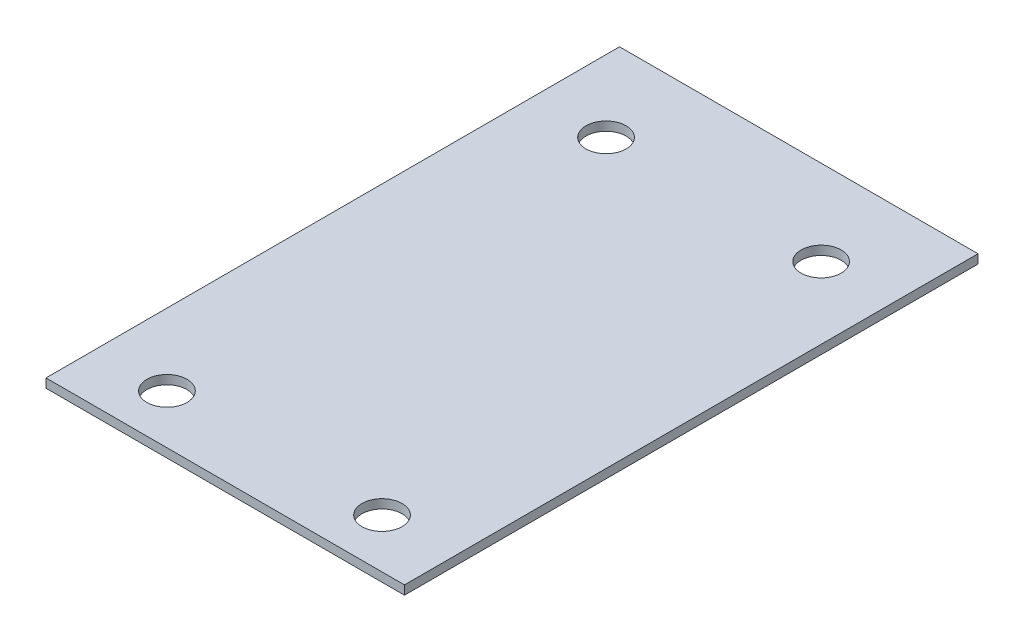
SolidWorks part; units mm, degrees
ref_plane "Front Plane" through (0, 0, 0) normal (0, 0, 1) x (1, 0, 0)
ref_plane "Top Plane" through (0, 0, 0) normal (0, 1, 0) x (1, 0, 0)
ref_plane "Right Plane" through (0, 0, 0) normal (1, 0, 0) x (0, 0, -1)
sketch "Sketch1" plane through (0, 0, 0) normal (0, 1, 0) x (1, 0, 0)
  line L0 (63.5, 203.2) -> (63.5, 0) construction
  line L1 (0, 0) -> (127, 0)
  line L2 (0, 0) -> (0, 203.2)
  line L3 (0, 203.2) -> (127, 203.2)
  line L4 (127, 0) -> (127, 203.2)
  circle A0 centre (25.4, 173.0248) radius 7.112
  circle A1 centre (25.4, 17.4498) radius 7.112
  circle A2 centre (101.6, 17.4498) radius 7.112
  circle A3 centre (101.6, 173.0248) radius 7.112
  dimension "D4" = 14.224
  dimension "D7" = 25.4
  dimension "D1" = 203.2
  dimension "D2" = 127
  dimension "D3" = 30.1752
  dimension "D5" = 155.575
  dimension "D6" = 25.4
extrude "Boss-Extrude2" add sketch "Sketch1" along normal blind 3.175
